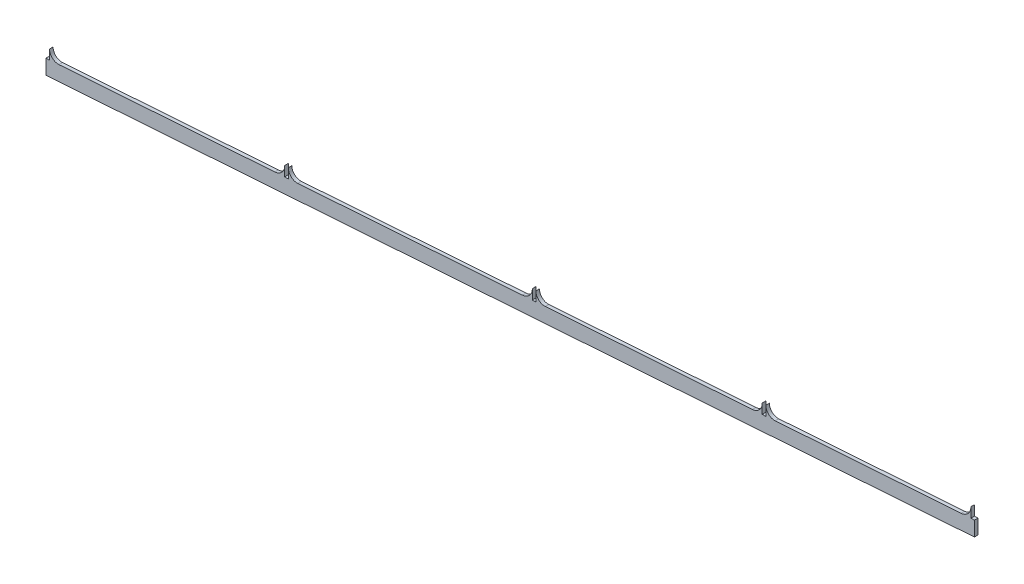
SolidWorks part; units mm, degrees
ref_plane "前视基准面" through (0, 0, 0) normal (0, 0, 1) x (1, 0, 0)
ref_plane "上视基准面" through (0, 0, 0) normal (0, 1, 0) x (1, 0, 0)
ref_plane "右视基准面" through (0, 0, 0) normal (1, 0, 0) x (0, 0, -1)
sketch "草图1" plane through (0, 0, 0) normal (0, 0, 1) x (1, 0, 0)
  line L0 (3.5937, 13.9396) -> (3.5937, 5.5396)
  line L1 (3.5937, 5.5396) -> (528.5937, 41.9255)
  line L2 (528.5937, 41.9255) -> (528.5937, 50.1869)
  line L3 (526.5937, 56.1869) -> (526.5937, 55.7855)
  line L4 (521.0085, 49.7998) -> (415.9394, 42.5179)
  line L5 (410.5937, 47.5059) -> (410.5937, 48.0087)
  line L6 (408.5937, 48.0087) -> (408.5937, 47.6073)
  line L7 (403.0085, 41.6217) -> (285.9394, 33.508)
  line L8 (280.5937, 38.496) -> (280.5937, 38.9989)
  line L9 (278.5937, 38.9989) -> (278.5937, 38.5975)
  line L10 (273.0085, 32.6118) -> (145.9394, 23.8051)
  line L11 (140.5937, 28.7931) -> (140.5937, 29.296)
  line L12 (138.5937, 29.296) -> (138.5937, 28.8945)
  line L13 (133.0085, 22.9089) -> (10.9394, 14.4487)
  line L14 (5.5937, 19.4367) -> (5.5937, 19.9396)
  line L15 (5.5937, 19.9396) -> (5.5937, 13.9396)
  line L16 (5.5937, 13.9396) -> (3.5937, 13.9396)
  line L17 (280.5937, 38.9989) -> (280.5937, 32.9989)
  line L18 (280.5937, 32.9989) -> (278.5937, 32.9989)
  line L19 (278.5937, 32.9989) -> (278.5937, 38.9989)
  line L20 (410.5937, 48.0087) -> (410.5937, 42.0087)
  line L21 (410.5937, 42.0087) -> (408.5937, 42.0087)
  line L22 (408.5937, 42.0087) -> (408.5937, 48.0087)
  line L23 (528.5937, 50.1869) -> (526.5937, 50.1869)
  line L24 (526.5937, 50.1869) -> (526.5937, 56.1869)
  line L25 (140.5937, 29.296) -> (140.5937, 23.296)
  line L26 (140.5937, 23.296) -> (138.5937, 23.296)
  line L27 (138.5937, 23.296) -> (138.5937, 29.296)
  arc A0 (410.5937, 47.5059) -> (415.9394, 42.5179) centre (415.5937, 47.5059) ccw
  arc A1 (521.0085, 49.7998) -> (526.5937, 55.7855) centre (520.5937, 55.7855) ccw
  arc A2 (280.5937, 38.496) -> (285.9394, 33.508) centre (285.5937, 38.496) ccw
  arc A3 (403.0085, 41.6217) -> (408.5937, 47.6073) centre (402.5937, 47.6073) ccw
  arc A4 (273.0085, 32.6118) -> (278.5937, 38.5975) centre (272.5937, 38.5975) ccw
  arc A5 (140.5937, 28.7931) -> (145.9394, 23.8051) centre (145.5937, 28.7931) ccw
  arc A6 (5.5937, 19.4367) -> (10.9394, 14.4487) centre (10.5937, 19.4367) ccw
  arc A7 (133.0085, 22.9089) -> (138.5937, 28.8945) centre (132.5937, 28.8945) ccw
extrude "凸台-拉伸1" add sketch "草图1" along normal blind 2 contours A7 L13 A6 L15 L16 L0 L1 L2 L23 L24 A1 L4 A0 L20 L21 L22 A3 L7 A2 L17 L18 L19 A4 L10 A5 L25 L26 L27
